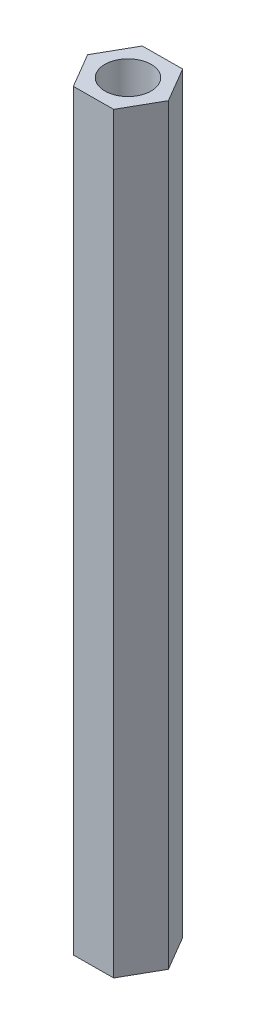
SolidWorks part; units mm, degrees
ref_plane "前视基准面" through (0, 0, 0) normal (0, 0, 1) x (1, 0, 0)
ref_plane "上视基准面" through (0, 0, 0) normal (0, 1, 0) x (1, 0, 0)
ref_plane "右视基准面" through (0, 0, 0) normal (1, 0, 0) x (0, 0, -1)
other "Configuration Table"
sketch "草图2" plane through (0, 0, 0) normal (0, 1, 0) x (1, 0, 0)
  line L1 (1.7108, 3.0122) -> (-1.7533, 2.9877)
  line L2 (-1.7533, 2.9877) -> (-3.464, -0.0245)
  line L3 (-3.464, -0.0245) -> (-1.7108, -3.0122)
  line L4 (-1.7108, -3.0122) -> (1.7533, -2.9877)
  line L5 (1.7533, -2.9877) -> (3.464, 0.0245)
  line L6 (3.464, 0.0245) -> (1.7108, 3.0122)
  circle A0 centre (0, 0) radius 3 construction
  circle A1 centre (0, 0) radius 2
  dimension "D2" = 4
  dimension "D1" = 6
extrude "凸台-拉伸1" add sketch "草图2" along normal blind 65 contours L5 L6 L1 L2 L3 L4 A1
